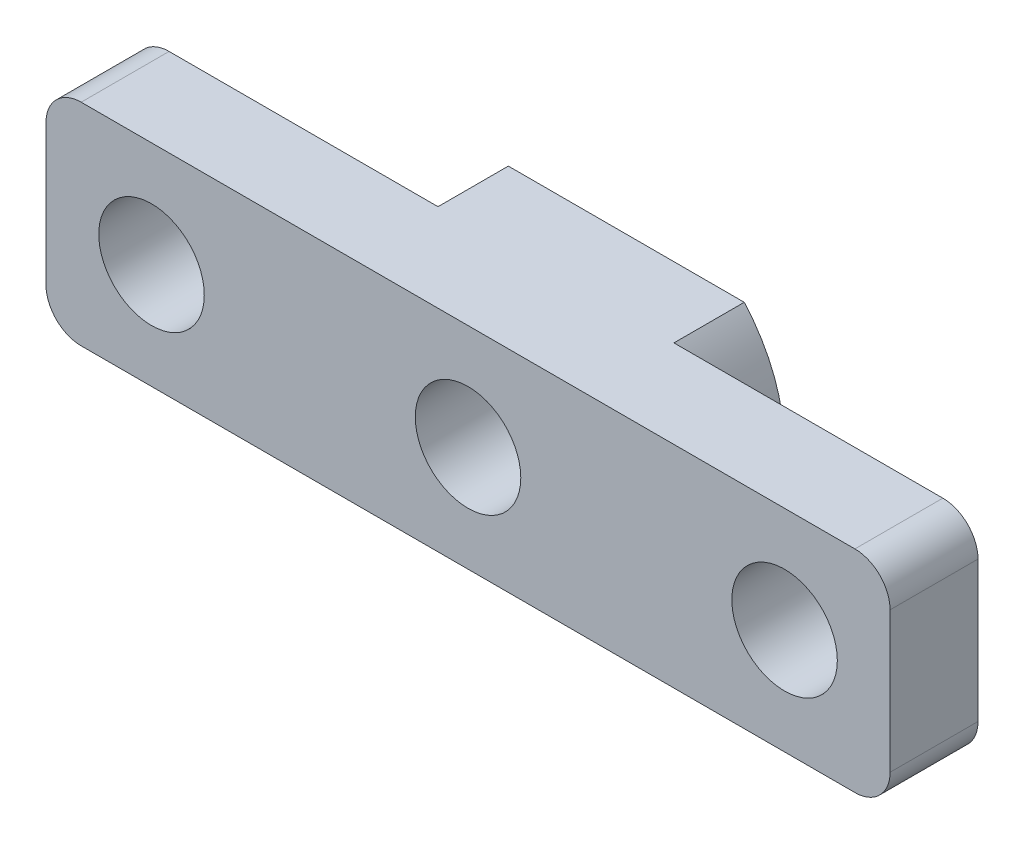
SolidWorks part; units mm, degrees
ref_plane "Front Plane" through (0, 0, 0) normal (0, 0, 1) x (1, 0, 0)
ref_plane "Top Plane" through (0, 0, 0) normal (0, 1, 0) x (1, 0, 0)
ref_plane "Right Plane" through (0, 0, 0) normal (1, 0, 0) x (0, 0, -1)
sketch "Sketch1" plane through (0, 0, 0) normal (0, 0, 1) x (1, 0, 0)
  line L1 (-3, 3) -> (21, 3)
  line L2 (-3, 3) -> (-3, -3)
  line L3 (-3, -3) -> (21, -3)
  line L4 (21, 3) -> (21, -3)
  circle A0 centre (0, 0) radius 1.5
  circle A1 centre (9, 0) radius 1.5
  circle A2 centre (18, 0) radius 1.5
  dimension "D1" = 3
  dimension "D3" = 12
  dimension "D4" = 12
  dimension "D5" = 3
  dimension "D6" = 3
  dimension "D2" = 3
extrude "Boss-Extrude2" add sketch "Sketch1" along normal blind 2.5
fillet "Fillet1" radius 1 1 edges at (-3, 3, 1.25)
fillet "Fillet2" radius 1 3 edges at (21, 3, 1.25) (21, -3, 1.25) (-3, -3, 1.25)
ref_plane "Plane1" through (0, 0, 0) normal (0, 0, -1) x (-1, 0, 0)
sketch "Sketch2" plane through (0, 0, 0) normal (0, 0, -1) x (-1, 0, 0)
  line L0 (2, -3) -> (-20, -3) construction
  line L1 (-20, 3) -> (2, 3) construction
  line L2 (-5.6459, -3) -> (-12.3541, -3)
  line L3 (-12.3541, 3) -> (-5.6459, 3)
  circle A0 centre (-9, 0) radius 1.5 construction
  circle A1 centre (-9, 0) radius 1.5
  arc A2 (-12.3541, 3) -> (-12.3541, -3) centre (-9, 0) ccw
  circle A3 centre (-9, 0) radius 4.5 construction
  arc A4 (-5.6459, -3) -> (-5.6459, 3) centre (-9, 0) ccw
  dimension "D1" = 3
extrude "Boss-Extrude3" add sketch "Sketch2" along normal blind 2
